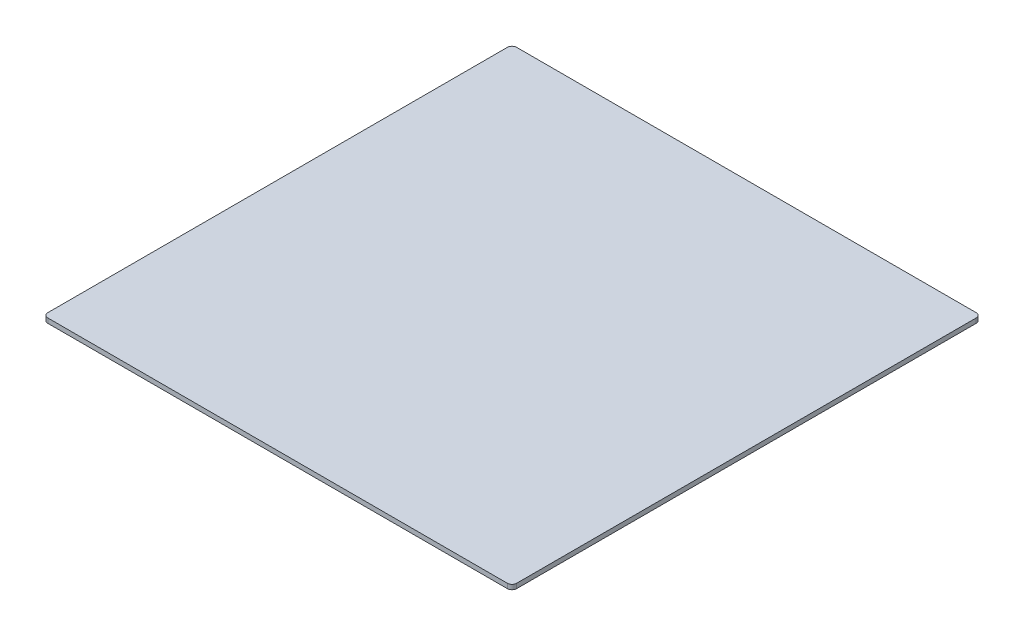
SolidWorks part; units mm, degrees
material "Cobre"
ref_plane "Plano frontal" through (0, 0, 0) normal (0, 0, 1) x (1, 0, 0)
ref_plane "Plano superior" through (0, 0, 0) normal (0, 1, 0) x (1, 0, 0)
ref_plane "Plano direito" through (0, 0, 0) normal (1, 0, 0) x (0, 0, -1)
sketch "Esboço1" plane through (0, 0, 0) normal (0, 1, 0) x (1, 0, 0)
  line L1 (-39.8051, 119.4454) -> (58.1949, 119.4454)
  line L2 (-40.8051, 118.4454) -> (-40.8051, 20.4454)
  line L3 (-39.8051, 19.4454) -> (58.1949, 19.4454)
  line L4 (59.1949, 118.4454) -> (59.1949, 20.4454)
  arc A0 (58.1949, 19.4454) -> (59.1949, 20.4454) centre (58.1949, 20.4454) ccw
  arc A1 (58.1949, 119.4454) -> (59.1949, 118.4454) centre (58.1949, 118.4454) cw
  arc A2 (-39.8051, 119.4454) -> (-40.8051, 118.4454) centre (-39.8051, 118.4454) ccw
  arc A3 (-40.8051, 20.4454) -> (-39.8051, 19.4454) centre (-39.8051, 20.4454) ccw
  dimension "D1" = 1
extrude "Ressalto-extrusão1" add sketch "Esboço1" along normal blind 1
